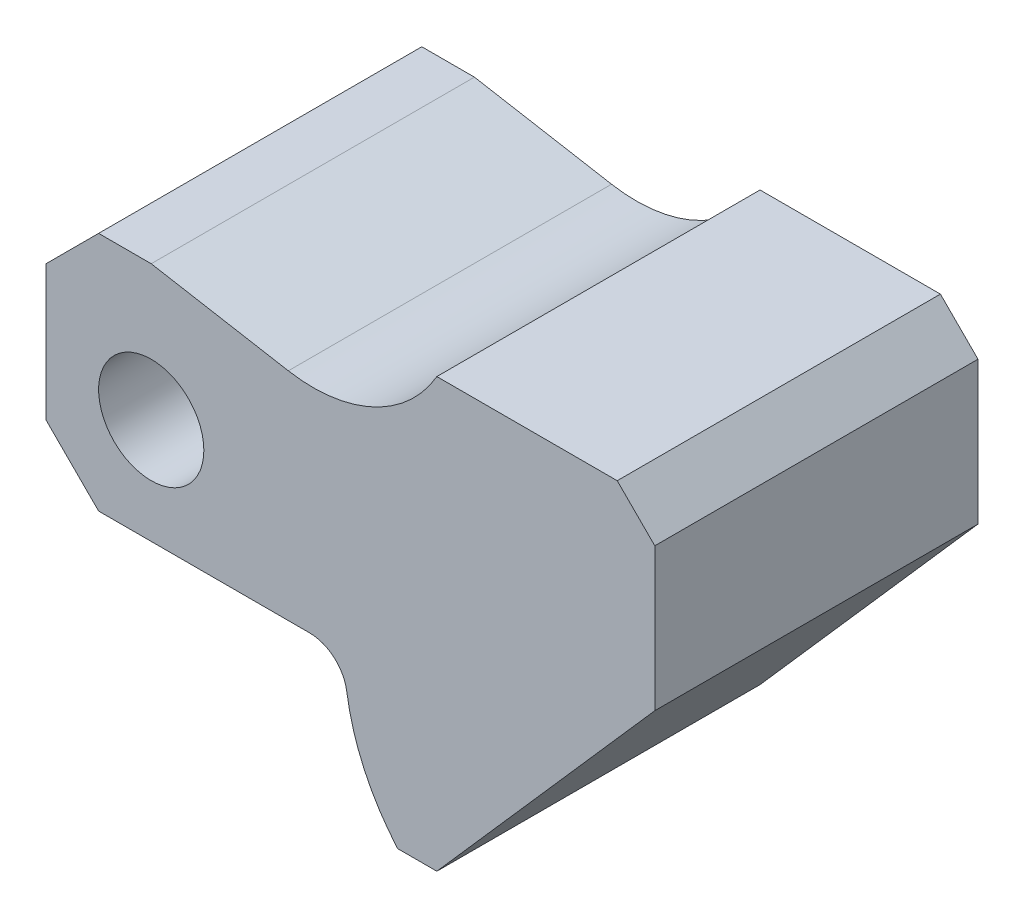
SolidWorks part; units mm, degrees
material "AISI 1020"
ref_plane "Front Plane" through (0, 0, 0) normal (0, 0, 1) x (1, 0, 0)
ref_plane "Top Plane" through (0, 0, 0) normal (0, 1, 0) x (1, 0, 0)
ref_plane "Right Plane" through (0, 0, 0) normal (1, 0, 0) x (0, 0, -1)
sketch "Sketch1" plane through (0, 0, 0) normal (0, 0, 1) x (1, 0, 0)
  line L0 (0, 0) -> (0, -18)
  line L1 (0, -18) -> (7, -25)
  line L2 (7, -25) -> (35.0666, -25)
  line L3 (46.7881, -44) -> (52, -44)
  line L4 (52, -44) -> (81, -11)
  line L5 (81, -11) -> (81, 8)
  line L6 (81, 8) -> (76, 13)
  line L7 (76, 13) -> (52, 13)
  line L8 (14, 7) -> (7, 7)
  line L10 (7, 7) -> (0, 0)
  line L11 (14, 7) -> (32.2431, 3.7833)
  arc A3 (32.2431, 3.7833) -> (52, 13) centre (35.5424, 22.4946) ccw
  arc A5 (35.0666, -25) -> (40.0123, -29.2647) centre (35.0666, -30) cw
  arc A6 (40.0123, -29.2647) -> (46.7881, -44) centre (68.697, -25) ccw
  circle A7 centre (14, -11) radius 7
  dimension "D10" = 24
  dimension "D14" = 5
  dimension "D15" = 29
  dimension "D16" = 19
  dimension "D20" = 14
  dimension "D1" = 7
  dimension "D2" = 7
  dimension "D3" = 32
  dimension "D4" = 45
  dimension "D5" = 45
  dimension "D6" = 14
  dimension "D7" = 45
  dimension "D8" = 5
  dimension "D9" = 29
  dimension "D11" = 29
  dimension "D12" = 19
  dimension "D13" = 81
  dimension "D17" = 10
  dimension "D18" = 57
  dimension "D19" = 19
  dimension "D21" = 14
  dimension "D22" = 14
extrude "Boss-Extrude1" add sketch "Sketch1" along normal blind 43 contours A5 A6 L3 L4 L5 L6 L7 A3 L11 L8 L10 L0 L1 L2 A7
